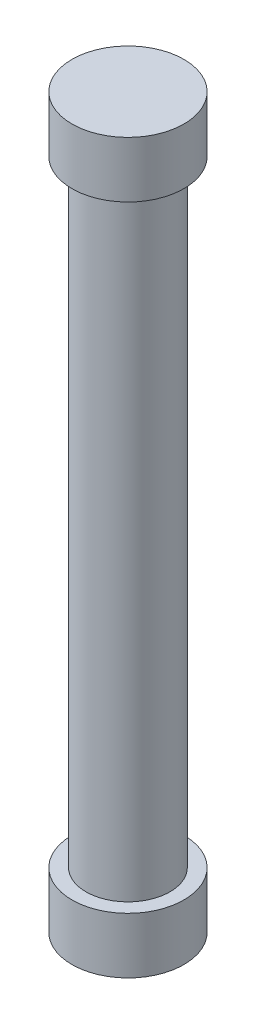
SolidWorks part; units mm, degrees
ref_plane "Front Plane" through (0, 0, 0) normal (0, 0, 1) x (1, 0, 0)
ref_plane "Top Plane" through (0, 0, 0) normal (0, 1, 0) x (1, 0, 0)
ref_plane "Right Plane" through (0, 0, 0) normal (1, 0, 0) x (0, 0, -1)
sketch "Sketch1" plane through (0, 0, 0) normal (0, 0, 1) x (1, 0, 0)
  line L0 (0, 0) -> (0, 2)
  line L1 (0, 2) -> (0.5, 2)
  line L2 (0.5, 2) -> (0.5, 24)
  line L3 (0.5, 24) -> (0, 24)
  line L4 (0, 24) -> (0, 26)
  line L5 (0, 26) -> (2, 26)
  line L6 (2, 26) -> (2, 0)
  line L7 (2, 0) -> (0, 0)
  dimension "D1" = 26
  dimension "D2" = 2
  dimension "D3" = 1.5
  dimension "D4" = 2
  dimension "D5" = 2
  dimension "D6" = 2
revolve "Revolve1" add sketch "Sketch1" angle 360 about L6
